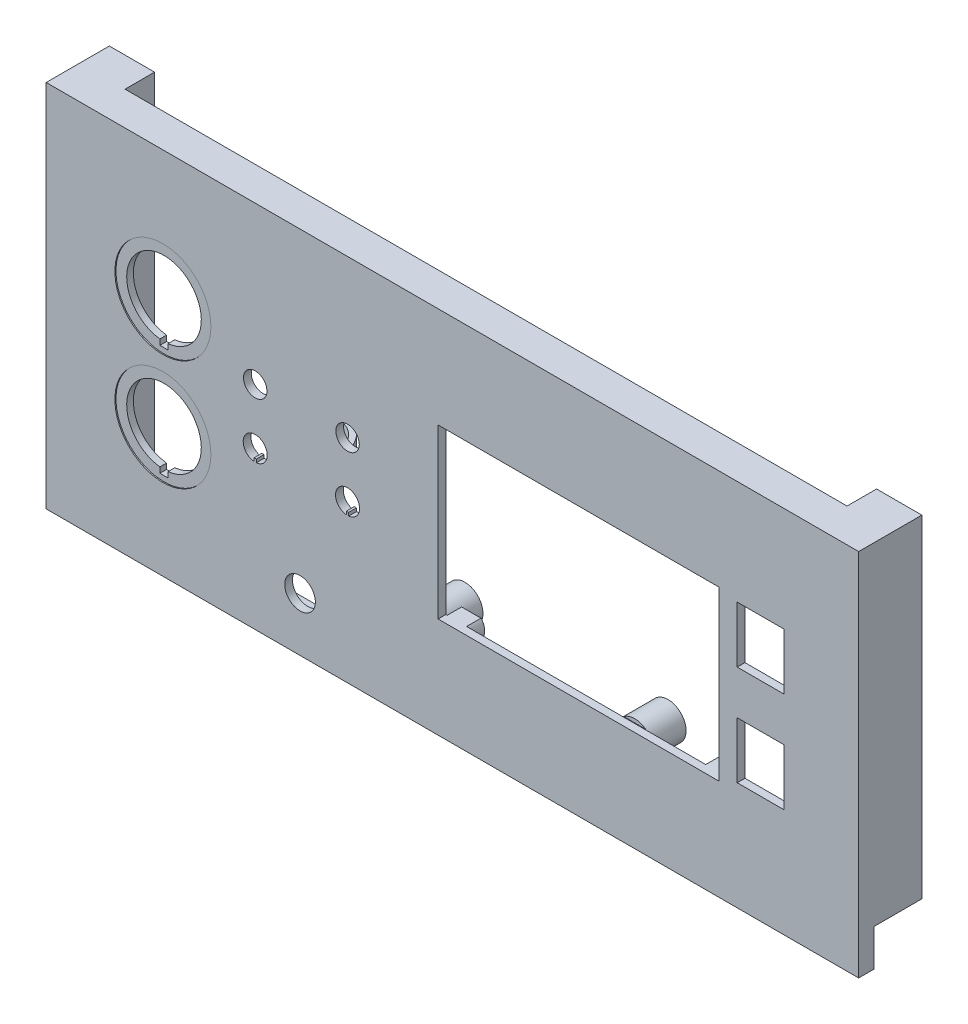
SolidWorks part; units mm, degrees
ref_plane "Front Plane" through (0, 0, 0) normal (0, 0, 1) x (1, 0, 0)
ref_plane "Top Plane" through (0, 0, 0) normal (0, 1, 0) x (1, 0, 0)
ref_plane "Right Plane" through (0, 0, 0) normal (1, 0, 0) x (0, 0, -1)
sketch "Sketch1" plane through (0, 0, 0) normal (0, 0, 1) x (1, 0, 0)
  line L1 (-110, 50) -> (110, 50)
  line L2 (-110, 50) -> (-110, -50)
  line L3 (-110, -50) -> (110, -50)
  line L4 (110, 50) -> (110, -50)
  line L5 (-110, 50) -> (110, -50) construction
  line L6 (-110, -50) -> (110, 50) construction
  point P0 (0, 0)
  dimension "D1" = 220
  dimension "D2" = 100
extrude "Front panel" add sketch "Sketch1" along normal blind 2.1
sketch "Sketch2" plane through (0, 0, 2.1) normal (0, 0, 1) x (1, 0, 0)
  line L0 (-78.3992, 15) -> (-78.3992, -15) construction
  line L1 (-79.4992, 4.9601) -> (-79.4992, 3.4601)
  line L2 (-79.4992, 3.4601) -> (-77.2992, 3.4601)
  line L3 (-77.2992, 3.4601) -> (-77.2992, 4.9601)
  line L4 (-79.4992, -25.0399) -> (-79.4992, -26.5399)
  line L5 (-79.4992, -26.5399) -> (-77.2992, -26.5399)
  line L6 (-77.2992, -26.5399) -> (-77.2992, -25.0399)
  arc A0 (-77.2992, 4.9601) -> (-79.4992, 4.9601) centre (-78.3992, 15) ccw
  arc A1 (-77.2992, -25.0399) -> (-79.4992, -25.0399) centre (-78.3992, -15) ccw
  point P4 (-78.3992, 0)
  point P10 (-78.3992, 3.4601)
  point P14 (-78.3992, -26.5399)
  dimension "D1" = 20.2
  dimension "D2" = 30
  dimension "D3" = 2.2
  dimension "D4" = 2.2
  dimension "D5" = 1.5
  dimension "D6" = 1.5
extrude "Start/stop" cut sketch "Sketch2" against normal through all
sketch "Sketch3" plane through (0, 0, 2.1) normal (0, 0, 1) x (1, 0, 0)
  line L0 (-78.3992, 15) -> (-78.3992, -15) construction
  line L1 (-53.6992, -10.7361) -> (-53.6992, -9.85)
  line L2 (-53.6992, -9.85) -> (-53.0992, -9.85)
  line L3 (-53.0992, -9.85) -> (-53.0992, -10.7361)
  line L4 (-28.6992, -10.7361) -> (-28.6992, -9.85)
  line L5 (-28.6992, -9.85) -> (-28.0992, -9.85)
  line L6 (-28.0992, -9.85) -> (-28.0992, -10.7361)
  line L7 (-53.3992, 7.5) -> (-53.3992, -7.5) construction
  arc A0 (-53.0992, -10.7361) -> (-53.6992, -10.7361) centre (-53.3992, -7.5) ccw
  circle A1 centre (-53.3992, 7.5) radius 3.175
  circle A2 centre (-28.3992, 7.5) radius 3.175
  circle A3 centre (-78.3992, 15) radius 10.1 construction
  circle A4 centre (-78.3992, -15) radius 10.1 construction
  circle A5 centre (-78.3992, 15) radius 10.1 construction
  circle A6 centre (-78.3992, -15) radius 10.1 construction
  arc A7 (-28.0992, -10.7361) -> (-28.6992, -10.7361) centre (-28.3992, -7.5) ccw
  point P9 (-53.3992, 0)
  point P14 (-78.3992, 0)
  point P17 (-53.3992, -9.85)
  point P22 (-28.3992, -9.85)
  dimension "D1" = 6.35
  dimension "D2" = 6.5
  dimension "D3" = 5.6
  dimension "D4" = 15
  dimension "D5" = 0.6
  dimension "D6" = 25
  dimension "D7" = 25
extrude "Mode select" cut sketch "Sketch3" against normal through all
sketch "Sketch4" plane through (0, 0, 2.1) normal (0, 0, 1) x (1, 0, 0)
  line L0 (-78.3992, 15) -> (-78.3992, -15) construction
  line L1 (-3.8858, 22.75) -> (72.1142, 22.75)
  line L2 (-3.8858, 22.75) -> (-3.8858, -22.75)
  line L3 (-3.8858, -22.75) -> (72.1142, -22.75)
  line L4 (72.1142, 22.75) -> (72.1142, -22.75)
  line L5 (-3.8858, 22.75) -> (72.1142, -22.75) construction
  line L6 (-3.8858, -22.75) -> (72.1142, 22.75) construction
  circle A4 centre (-78.3992, -15) radius 10.1 construction
  circle A5 centre (-78.3992, -15) radius 10.1 construction
  point P0 (34.1142, 0)
  point P10 (-78.3992, 0)
  dimension "D1" = 45.5
  dimension "D2" = 76
extrude "LCD cutout" cut sketch "Sketch4" against normal through all
sketch "Sketch5" plane through (0, 0, 2.1) normal (0, 0, 1) x (1, 0, 0)
  circle A0 centre (213.3388, 0) radius 11.25
  point P4 (-144.7898, 0)
  dimension "D1" = 22.5
extrude "E-stop cutout" [suppressed] cut sketch "Sketch5" against normal through all
sketch "Sketch6" plane through (0, 0, 2.1) normal (0, 0, 1) x (1, 0, 0)
  line L0 (75.6542, -22.75) -> (159.8496, -22.75) construction
  line L1 (77.1142, 21.7025) -> (89.8142, 21.7025)
  line L2 (77.1142, 21.7025) -> (77.1142, 6.4625)
  line L3 (77.1142, 6.4625) -> (89.8142, 6.4625)
  line L4 (89.8142, 21.7025) -> (89.8142, 6.4625)
  line L5 (77.1142, 21.7025) -> (89.8142, 6.4625) construction
  line L6 (77.1142, 6.4625) -> (89.8142, 21.7025) construction
  line L7 (77.1142, -5.415) -> (89.8142, -5.415)
  line L8 (77.1142, -5.415) -> (77.1142, -20.655)
  line L9 (77.1142, -20.655) -> (89.8142, -20.655)
  line L10 (89.8142, -5.415) -> (89.8142, -20.655)
  line L11 (77.1142, -5.415) -> (89.8142, -20.655) construction
  line L12 (77.1142, -20.655) -> (89.8142, -5.415) construction
  line L13 (-3.8858, -22.75) -> (72.1142, -22.75) construction
  line L14 (75.6542, 22.75) -> (158.6931, 22.75) construction
  line L15 (72.1142, 22.75) -> (-3.8858, 22.75) construction
  line L16 (75.6542, 22.75) -> (75.6542, 20.3374) construction
  line L17 (75.6542, -22.75) -> (75.6542, 12.4166) construction
  line L18 (72.1142, -22.75) -> (72.1142, 22.75) construction
  point P0 (83.4642, 14.0825)
  point P5 (83.4642, -13.035)
  point P18 (0, 0)
  dimension "D1" = 15.24
  dimension "D2" = 12.7
  dimension "D3" = 2.095
  dimension "D4" = 2.095
  dimension "D5" = 1.46
  dimension "D6" = 1.46
  dimension "D7" = 5
extrude "LCD pushbuttons" cut sketch "Sketch6" against normal through all
sketch "Sketch7" plane through (0, 0, 2.1) normal (0, 0, 1) x (1, 0, 0)
  line L1 (-18.8982, 43.8567) -> (72.1018, 43.8567) construction
  line L2 (-18.8982, 43.8567) -> (-18.8982, -45.1433) construction
  line L3 (-18.8982, -45.1433) -> (72.1018, -45.1433) construction
  line L4 (72.1018, 43.8567) -> (72.1018, -45.1433) construction
  line L5 (-18.8982, 43.8567) -> (72.1018, -45.1433) construction
  line L6 (-18.8982, -45.1433) -> (72.1018, 43.8567) construction
  point P0 (26.6018, -0.6433)
  dimension "D1" = 89
  dimension "D2" = 91
sketch "Sketch8" plane through (0, 0, 0) normal (0, 0, -1) x (-1, 0, 0)
  line L0 (-110, -50) -> (-110, 50) construction
  line L1 (110, 50) -> (110, -50) construction
  line L2 (-110, -40) -> (-110, 50)
  line L3 (110, 50) -> (110, -40)
  line L4 (-110, -40) -> (-97.75, -40)
  line L5 (-97.75, -40) -> (-97.75, 50)
  line L6 (-110, 50) -> (110, 50) construction
  line L7 (-97.75, 50) -> (-110, 50)
  line L8 (97.75, -40) -> (110, -40)
  line L9 (97.75, -40) -> (97.75, 50)
  line L10 (97.75, 50) -> (110, 50)
  line L11 (110, -50) -> (-110, -50) construction
  line L12 (100.75, -37) -> (100.75, 47)
  line L13 (100.75, 47) -> (107, 47)
  line L14 (107, 47) -> (107, -37)
  line L15 (100.75, -37) -> (107, -37)
  line L16 (-100.75, -37) -> (-100.75, 47)
  line L17 (-100.75, 47) -> (-107, 47)
  line L18 (-107, -37) -> (-107, 47)
  line L19 (-107, -37) -> (-100.75, -37)
  dimension "D1" = 12.25
  dimension "D2" = 10
  dimension "D3" = 3
extrude "Boss-Extrude1" add sketch "Sketch8" along normal blind 15
sketch "Sketch9" plane through (0, 0, 0) normal (0, 0, -1) x (-1, 0, 0)
  line L0 (-41.2738, -32.5) -> (13.7262, -32.5) construction
  line L1 (13.7262, -32.5) -> (13.7262, 17.5) construction
  line L2 (-41.2738, -32.5) -> (-41.2738, 32.5) construction
  circle A0 centre (-41.2738, -32.5) radius 2.9
  circle A1 centre (-41.2738, 32.5) radius 2.9
  circle A2 centre (13.7262, 17.5) radius 2.9
  circle A3 centre (13.7262, -32.5) radius 2.9
  circle A4 centre (-41.2738, -32.5) radius 4.9
  circle A5 centre (13.7262, -32.5) radius 4.9
  circle A6 centre (13.7262, 17.5) radius 4.9
  circle A7 centre (-41.2738, 32.5) radius 4.9
  point P16 (-41.2738, 0)
  dimension "D1" = 5.8
  dimension "D5" = 2
  dimension "D2" = 50
  dimension "D3" = 65
  dimension "D4" = 55
  dimension "D6" = 2
extrude "Boss-Extrude2" add sketch "Sketch9" along normal blind 15 contours A4 | A5 | A7 | A6
sketch "Sketch11" plane through (0, 0, 0) normal (0, 0, -1) x (-1, 0, 0)
  line L0 (-72.1142, 22.75) -> (3.8858, -22.75) construction
  line L1 (-72.1142, -22.75) -> (3.8858, 22.75) construction
  line L2 (-69.1142, 25.25) -> (0.8858, -25.25) construction
  line L3 (0.8858, 25.25) -> (-69.1142, -25.25) construction
  line L4 (3.8858, -22.75) -> (-72.1142, -22.75) construction
  line L5 (-72.1142, 22.75) -> (3.8858, 22.75) construction
  line L6 (-71.7392, 22.75) -> (-66.4892, 22.75)
  line L7 (3.5108, -22.75) -> (-1.7392, -22.75)
  line L8 (-66.4892, -22.75) -> (-71.7392, -22.75)
  line L9 (-1.7392, 22.75) -> (3.5108, 22.75)
  circle A0 centre (-69.1142, 25.25) radius 1.625
  circle A1 centre (0.8858, 25.25) radius 1.625
  circle A2 centre (-69.1142, -25.25) radius 1.625
  circle A3 centre (0.8858, -25.25) radius 1.625
  arc A4 (-71.7392, -22.75) -> (-66.4892, -22.75) centre (-69.1142, -25.25) ccw
  arc A5 (-1.7392, -22.75) -> (3.5108, -22.75) centre (0.8858, -25.25) ccw
  arc A6 (3.5108, 22.75) -> (-1.7392, 22.75) centre (0.8858, 25.25) ccw
  arc A7 (-66.4892, 22.75) -> (-71.7392, 22.75) centre (-69.1142, 25.25) ccw
  circle A9 centre (0.8858, -25.25) radius 3.625 construction
  circle A10 centre (-69.1142, -25.25) radius 3.625 construction
  circle A11 centre (-69.1142, 25.25) radius 3.625 construction
  circle A12 centre (0.8858, 25.25) radius 3.625 construction
  point P9 (-65.6476, 26.3098)
  point P11 (-65.6476, -24.1902)
  point P15 (4.3524, 26.3098)
  point P23 (-34.1142, 0)
  point P24 (4.3524, -24.1902)
  dimension "D1" = 3.25
  dimension "D2" = 70
  dimension "D3" = 50.5
  dimension "D4" = 2
extrude "Boss-Extrude3" add sketch "Sketch11" along normal up to surface (3.9 mm away)
sketch "Sketch12" plane through (0, 0, 0) normal (0, 0, -1) x (-1, 0, 0)
  line L0 (-44.2403, -28.6) -> (-38.3073, -28.6)
  circle A0 centre (-41.2738, -32.5) radius 4.9 construction
  arc A1 (-38.3073, -28.6) -> (-44.2403, -28.6) centre (-41.2738, -32.5) ccw
  dimension "D1" = 1
extrude "Cut-Extrude1" cut sketch "Sketch12" along normal blind 6
sketch "Sketch13" plane through (0, 0, -15) normal (0, 0, -1) x (-1, 0, 0)
  circle A0 centre (13.7262, -32.5) radius 2.875
  circle A1 centre (-41.2738, -32.5) radius 2.875
  circle A2 centre (-41.2738, 32.5) radius 2.875
  circle A3 centre (13.7262, 17.5) radius 2.875
  circle A4 centre (13.7262, 17.5) radius 4.9 construction
  circle A5 centre (-41.2738, 32.5) radius 4.9 construction
  circle A7 centre (-41.2738, -32.5) radius 4.9 construction
  dimension "D1" = 5.75
extrude "Cut-Extrude2" cut sketch "Sketch13" against normal blind 4.7
sketch "Sketch14" plane through (0, 0, 0) normal (0, 0, -1) x (-1, 0, 0)
  line L0 (-97.75, -40) -> (-97.75, 50) construction
  line L1 (97.75, 50) -> (-97.75, 50)
  line L2 (97.75, 50) -> (97.75, 47)
  line L3 (97.75, 47) -> (-97.75, 47)
  line L4 (-97.75, 50) -> (-97.75, 47)
  dimension "D1" = 3
extrude "Boss-Extrude4" add sketch "Sketch14" along normal blind 7
sketch "Sketch17" plane through (0, 0, 2.1) normal (0, 0, 1) x (1, 0, 0)
  circle A3 centre (-78.3992, 15) radius 13
  circle A4 centre (-78.3992, -15) radius 13
  circle A5 centre (-78.3992, -15) radius 10.1 construction
  circle A6 centre (-78.3992, 15) radius 10.1 construction
  dimension "D1" = 26
extrude "Cut-Extrude3" cut sketch "Sketch17" against normal blind 0.3
sketch "Sketch18" plane through (0, 0, 0) normal (0, 0, -1) x (-1, 0, 0)
  line L1 (-110, -50) -> (110, -50)
  line L2 (-110, -50) -> (-110, -40)
  line L3 (-110, -40) -> (110, -40)
  line L4 (110, -50) -> (110, -40)
extrude "Boss-Extrude5" add sketch "Sketch18" along normal blind 2
sketch "Sketch19" plane through (0, 0, 2.1) normal (0, 0, 1) x (1, 0, 0)
  circle A0 centre (-41.2592, -35.4024) radius 4.15
  dimension "D1" = 8.3
extrude "Cut-Extrude4" cut sketch "Sketch19" against normal through all
sketch "Sketch20" plane through (0, 50, 0) normal (0, 1, 0) x (1, 0, 0)
  line L1 (-48.8545, 0) -> (-47.3417, 0)
  line L2 (-30.8289, 0) -> (-32.3417, 0)
  line L3 (-97.75, 0) -> (97.75, 0) construction
  arc A0 (-30.8289, 0) -> (-48.8545, 0) centre (-39.8417, -1.0769) ccw
  arc A1 (-32.3417, 0) -> (-47.3417, 0) centre (-39.8417, -1.0769) ccw
  arc A3 (-32.3183, -0.178) -> (-47.3651, -0.178) centre (-39.8417, -1.0769) ccw construction
  point P8 (-39.8417, 8)
  dimension "D2" = 15
  dimension "D1" = 1.5
extrude "Boss-Extrude6" add sketch "Sketch20" against normal blind 3 from offset 48 separate body
